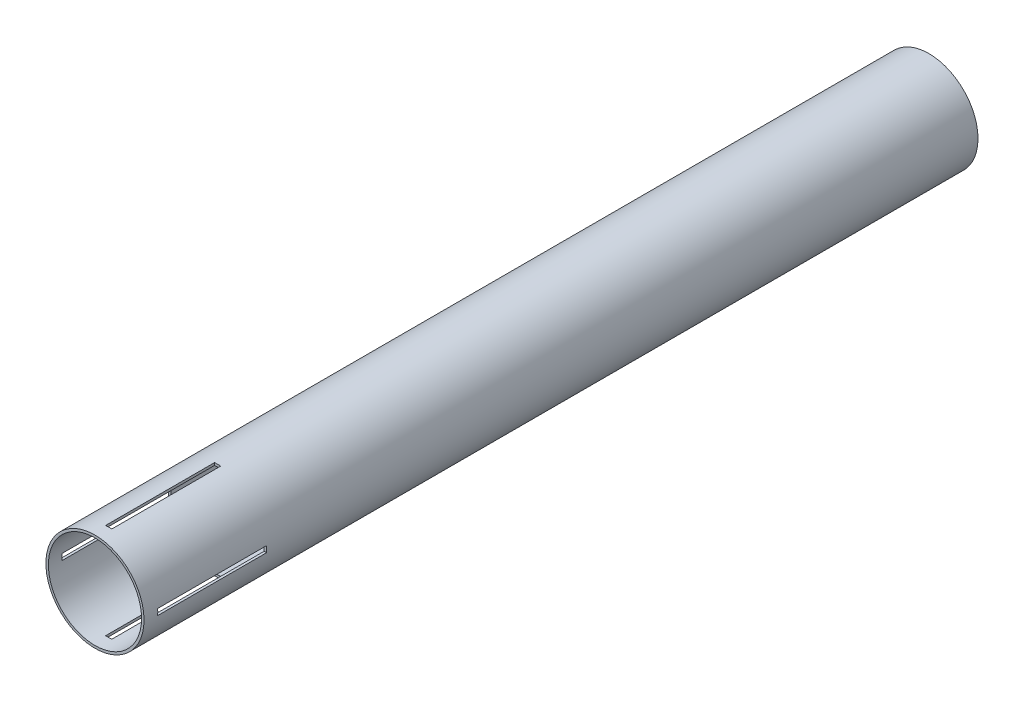
SolidWorks part; units mm, degrees
other "Markup1"
sketch "Sketch5" plane through (50.8, 50.8, 0) normal (0.1901, 0.9762, -0.1044) x (0.0697, 0.0927, 0.9933)
ref_plane "Front Plane" through (0, 0, 0) normal (0, 0, 1) x (1, 0, 0)
ref_plane "Top Plane" through (0, 0, 0) normal (0, 1, 0) x (1, 0, 0)
ref_plane "Right Plane" through (0, 0, 0) normal (1, 0, 0) x (0, 0, -1)
sketch "Sketch1" plane through (0, 0, 0) normal (0, 0, 1) x (1, 0, 0)
  circle A0 centre (0, 0) radius 50.8
  circle A1 centre (0, 0) radius 48.26
  dimension "D1" = 101.6
  dimension "D2" = 2.54
extrude "Boss-Extrude1" add sketch "Sketch1" along normal blind 863.6
sketch "Sketch2" plane through (0, 0, 863.6) normal (0, 0, 1) x (1, 0, 0)
  line L2 (-3.175, 50.7007) -> (-3.175, 48.1554)
  line L4 (3.175, 50.7007) -> (3.175, 48.1554)
  line L5 (-50.7007, 3.175) -> (-48.1554, 3.175)
  line L7 (-50.7007, -3.175) -> (-48.1554, -3.175)
  line L12 (48.1554, 3.175) -> (50.7007, 3.175)
  line L13 (48.1554, -3.175) -> (50.7007, -3.175)
  line L14 (3.175, -48.1554) -> (3.175, -50.7007)
  line L15 (-3.175, -48.1554) -> (-3.175, -50.7007)
  circle A0 centre (0, 0) radius 50.8 construction
  circle A1 centre (0, 0) radius 48.26 construction
  arc A2 (3.175, 50.7007) -> (-3.175, 50.7007) centre (0, 0) ccw
  arc A3 (3.175, 48.1554) -> (-3.175, 48.1554) centre (0, 0) ccw
  arc A4 (-48.1554, 3.175) -> (-48.1554, -3.175) centre (0, 0) ccw
  arc A5 (-50.7007, 3.175) -> (-50.7007, -3.175) centre (0, 0) ccw
  arc A6 (-3.175, -50.7007) -> (3.175, -50.7007) centre (0, 0) ccw
  arc A7 (-3.175, -48.1554) -> (3.175, -48.1554) centre (0, 0) ccw
  arc A8 (50.7007, -3.175) -> (50.7007, 3.175) centre (0, 0) ccw
  arc A9 (48.1554, -3.175) -> (48.1554, 3.175) centre (0, 0) ccw
  dimension "D1" = 6.35
extrude "Cut-Extrude1" cut sketch "Sketch2" against normal blind 127
sketch "Sketch4" plane through (0, 0, 863.6) normal (0, 0, 1) x (1, 0, 0)
  line L0 (50.7007, 3.175) -> (48.1554, 3.175) construction
  line L1 (48.1554, -3.175) -> (50.7007, -3.175) construction
  line L2 (-3.175, 50.7007) -> (-3.175, 48.1554)
  line L3 (3.175, 48.1554) -> (3.175, 50.7007)
  line L4 (-3.175, 50.7007) -> (-3.175, 48.1554)
  line L5 (3.175, 48.1554) -> (3.175, 50.7007)
  line L6 (3.175, -50.7007) -> (3.175, -48.1554) construction
  line L7 (-3.175, -48.1554) -> (-3.175, -50.7007) construction
  line L8 (-48.1554, 3.175) -> (-50.7007, 3.175) construction
  line L9 (-50.7007, -3.175) -> (-48.1554, -3.175) construction
  line L10 (50.7007, 3.175) -> (48.1554, 3.175)
  line L11 (48.1554, -3.175) -> (50.7007, -3.175)
  line L12 (3.175, -50.7007) -> (3.175, -48.1554)
  line L13 (-3.175, -48.1554) -> (-3.175, -50.7007)
  line L14 (-48.1554, 3.175) -> (-50.7007, 3.175)
  line L15 (-50.7007, -3.175) -> (-48.1554, -3.175)
  arc A0 (50.7007, -3.175) -> (50.7007, 3.175) centre (0, 0) ccw construction
  arc A1 (48.1554, -3.175) -> (48.1554, 3.175) centre (0, 0) ccw construction
  arc A2 (3.175, 50.7007) -> (-3.175, 50.7007) centre (0, 0) ccw
  arc A3 (3.175, 48.1554) -> (-3.175, 48.1554) centre (0, 0) ccw
  arc A4 (3.175, 50.7007) -> (-3.175, 50.7007) centre (0, 0) ccw
  arc A5 (3.175, 48.1554) -> (-3.175, 48.1554) centre (0, 0) ccw
  arc A6 (-3.175, -50.7007) -> (3.175, -50.7007) centre (0, 0) ccw construction
  arc A7 (-3.175, -48.1554) -> (3.175, -48.1554) centre (0, 0) ccw construction
  arc A8 (-48.1554, 3.175) -> (-48.1554, -3.175) centre (0, 0) ccw construction
  arc A9 (-50.7007, 3.175) -> (-50.7007, -3.175) centre (0, 0) ccw construction
  arc A10 (50.7007, -3.175) -> (50.7007, 3.175) centre (0, 0) ccw
  arc A11 (48.1554, -3.175) -> (48.1554, 3.175) centre (0, 0) ccw
  arc A12 (-3.175, -50.7007) -> (3.175, -50.7007) centre (0, 0) ccw
  arc A13 (-3.175, -48.1554) -> (3.175, -48.1554) centre (0, 0) ccw
  arc A14 (-48.1554, 3.175) -> (-48.1554, -3.175) centre (0, 0) ccw
  arc A15 (-50.7007, 3.175) -> (-50.7007, -3.175) centre (0, 0) ccw
  dimension "D1" = 0
extrude "Boss-Extrude2" add sketch "Sketch4" against normal blind 14.224
